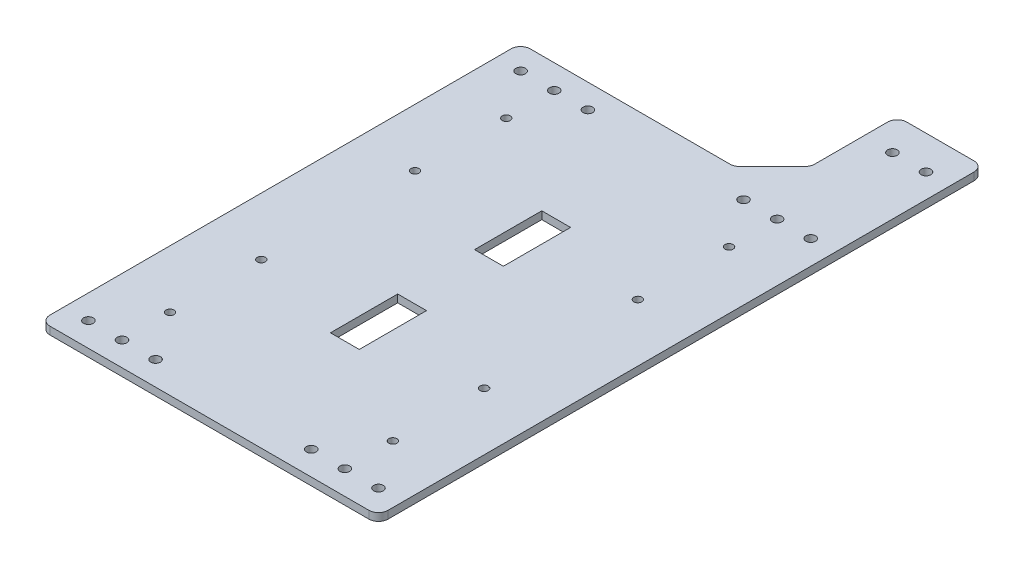
SolidWorks part; units mm, degrees
material "3.3549 (EN-AW 5182)"
ref_plane "Front Plane" through (0, 0, 0) normal (0, 0, 1) x (1, 0, 0)
ref_plane "Top Plane" through (0, 0, 0) normal (0, 1, 0) x (1, 0, 0)
ref_plane "Right Plane" through (0, 0, 0) normal (1, 0, 0) x (0, 0, -1)
sketch "Sketch1" plane through (0, 0, 0) normal (0, 1, 0) x (1, 0, 0)
  line L1 (-123, 125) -> (8, 125)
  line L2 (-123, 125) -> (-123, -125)
  line L3 (-53, -125) -> (53, -125)
  line L4 (53, 125) -> (53, -125)
  line L7 (53, 125) -> (53, 190)
  line L8 (53, 190) -> (8, 190)
  line L9 (8, 190) -> (8, 125)
  line L10 (-123, -125) -> (-53, -125)
  point P4 (0, -125)
  point P5 (-123, 0)
  dimension "D1" = 176
  dimension "D2" = 250
  dimension "D3" = 65
  dimension "D4" = 45
extrude "Boss-Extrude1" add sketch "Sketch1" along normal blind 4
sketch "Sketch2" plane through (0, 4, 0) normal (0, 1, 0) x (1, 0, 0)
  line L0 (-57.5, 125) -> (-57.5, -125) construction
  line L1 (8, 125) -> (-123, 125) construction
  line L2 (-123, -125) -> (53, -125) construction
  line L3 (0, 0) -> (78, 0) construction
  line L4 (-123, 125) -> (-123, -125) construction
  line L5 (53, -125) -> (53, 190) construction
  line L6 (-75.5, -112.5) -> (-110.5, -112.5) construction
  line L8 (5.5, -112.5) -> (40.5, -112.5) construction
  line L9 (5.5, 112.5) -> (40.5, 112.5) construction
  line L11 (-75.5, 112.5) -> (-110.5, 112.5) construction
  circle A0 centre (-110.5, -112.5) radius 2.5
  circle A1 centre (-75.5, -112.5) radius 2.5
  circle A8 centre (-93, -112.5) radius 2.5
  circle A12 centre (-93, -87.5) radius 2.1
  circle A16 centre (5.5, -112.5) radius 2.5
  circle A17 centre (23, -112.5) radius 2.5
  circle A18 centre (40.5, -112.5) radius 2.5
  circle A19 centre (23, -87.5) radius 2.1
  circle A20 centre (23, 87.5) radius 2.1
  circle A21 centre (40.5, 112.5) radius 2.5
  circle A22 centre (23, 112.5) radius 2.5
  circle A23 centre (5.5, 112.5) radius 2.5
  circle A24 centre (-93, 87.5) radius 2.1
  circle A25 centre (-93, 112.5) radius 2.5
  circle A26 centre (-75.5, 112.5) radius 2.5
  circle A27 centre (-110.5, 112.5) radius 2.5
  circle A30 centre (40.5, 172.5) radius 2.5
  circle A31 centre (23, 172.5) radius 2.5
  dimension "D1" = 5
  dimension "D6" = 4.2
  dimension "D7" = 12.5
  dimension "D9" = 60
  dimension "D2" = 12.5
  dimension "D3" = 35
  dimension "D4" = 12.5
  dimension "D5" = 25
  dimension "D8" = 25
extrude "Cut-Extrude1" cut sketch "Sketch2" against normal through all
sketch "Sketch3" plane through (0, 0, 0) normal (0, -1, 0) x (1, 0, 0)
  line L0 (-123, 125) -> (53, 125) construction
  line L1 (-42, 55) -> (-27, 55)
  line L2 (-42, 55) -> (-42, 20)
  line L3 (-42, 20) -> (-27, 20)
  line L4 (-27, 55) -> (-27, 20)
  line L5 (53, 0) -> (-123, 0) construction
  line L6 (53, 125) -> (53, -190) construction
  line L7 (-123, -125) -> (-123, 125) construction
  line L8 (-27, -55) -> (-27, -20)
  line L9 (-42, -20) -> (-27, -20)
  line L10 (-42, -55) -> (-42, -20)
  line L11 (-42, -55) -> (-27, -55)
  line L12 (53, 125) -> (53, -190) construction
  point P16 (-123, 0)
  dimension "D1" = 70
  dimension "D2" = 35
  dimension "D3" = 15
  dimension "D4" = 80
extrude "Cut-Extrude2" cut sketch "Sketch3" against normal through all contours L10 L11 L8 L3 | L2 L9 L4 L1
sketch "Sketch4" plane through (0, 0, 0) normal (0, -1, 0) x (1, 0, 0)
  line L0 (-103, 0) -> (53, 0) construction
  line L3 (2.0229, 0) -> (-35, 0) construction
  line L4 (-35, 0) -> (-35, 125) construction
  line L6 (-93, 87.5) -> (-93, -87.5) construction
  line L7 (-123, -125) -> (-123, 125) construction
  line L8 (53, 125) -> (53, -190) construction
  circle A0 centre (-93, 40) radius 2.1
  circle A25 centre (-93, -40) radius 2.1
  circle A26 centre (23, -40) radius 2.1
  circle A29 centre (23, 40) radius 2.1
  circle A30 centre (-93, -87.5) radius 2.1 construction
  dimension "D1" = 4.2
  dimension "D2" = 40
extrude "Cut-Extrude3" cut sketch "Sketch4" against normal blind 10
chamfer "Chamfer1" distance 20 angle 45 1 edges at (8, 2, -125)
fillet "Fillet1" radius 5 7 edges at (53, 2, 125) (-123, 2, 125) (-123, 2, -125) (53, 2, -190) (8, 2, -190) (-12, 2, -125) (8, 2, -145)
ref_plane "Plane3" through (-35, 0, 0) normal (-1, 0, 0) x (0, 0, 1)
